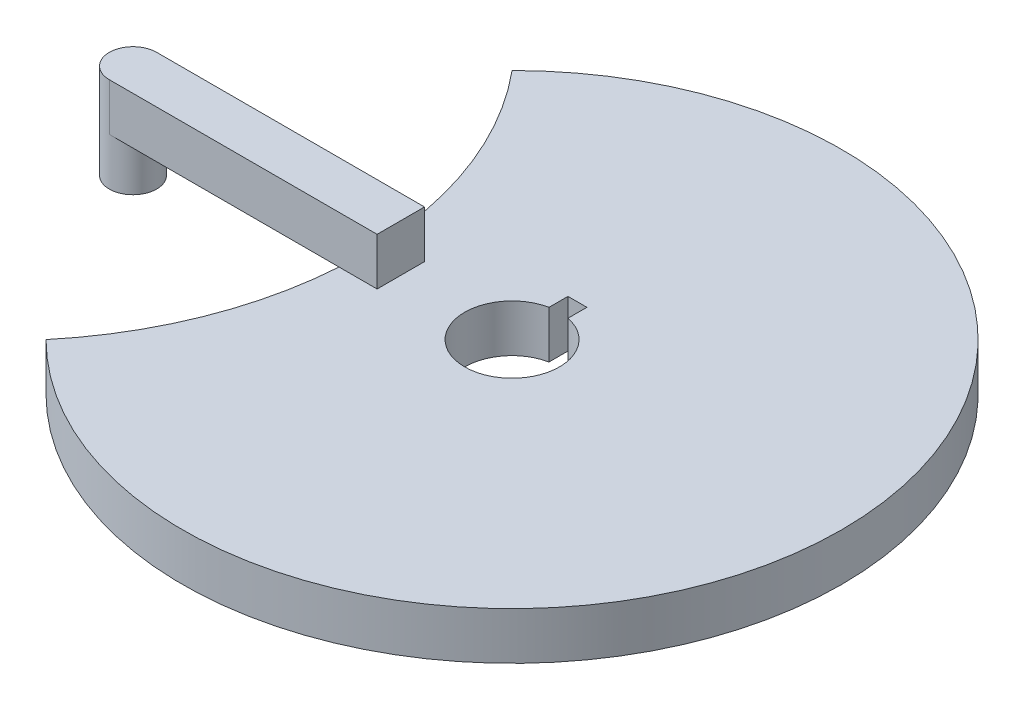
SolidWorks part; units mm, degrees
ref_plane "前视基准面" through (0, 0, 0) normal (0, 0, 1) x (1, 0, 0)
ref_plane "上视基准面" through (0, 0, 0) normal (0, 1, 0) x (1, 0, 0)
ref_plane "右视基准面" through (0, 0, 0) normal (1, 0, 0) x (0, 0, -1)
sketch "草图1" plane through (0, 0, 0) normal (0, 1, 0) x (1, 0, 0)
  line L0 (-129.4458, 0) -> (166.3539, 0) construction
  line L1 (0, 112.5965) -> (0, -118.4804) construction
  line L2 (-2, 9.798) -> (-2, 13.798)
  line L3 (-2, 13.798) -> (2, 13.798)
  line L4 (2, 9.798) -> (2, 13.798)
  line L5 (-49.1802, 49.1802) -> (0, 0) construction
  line L6 (0, 0) -> (-49.1802, -49.1802) construction
  arc A0 (-49.1802, -49.1802) -> (-49.1802, 49.1802) centre (0, 0) ccw
  arc A1 (-2, 9.798) -> (2, 9.798) centre (0, 0) ccw
  arc A5 (-49.1802, -49.1802) -> (-49.1802, 49.1802) centre (-108.1238, 0) ccw
  point P13 (0, 13.798)
  dimension "D1" = 4
  dimension "D2" = 90
  dimension "D3" = 10
  dimension "D4" = 4
extrude "凸台-拉伸1" add sketch "草图1" along normal blind 10
sketch "草图4" plane through (0, 10, 0) normal (0, 1, 0) x (1, 0, 0)
  line L0 (-80, 5) -> (-23.4813, 5)
  line L1 (-23.4813, 5) -> (-23.4813, -5)
  line L2 (-23.4813, -5) -> (-80, -5)
  arc A0 (-80, 5) -> (-80, -5) centre (-80, 0) ccw
  dimension "D1" = 80
extrude "凸台-拉伸5" add sketch "草图4" along normal blind 10
sketch "草图5" plane through (0, 10, 0) normal (0, -1, 0) x (1, 0, 0)
  circle A0 centre (-80, 0) radius 5
extrude "凸台-拉伸6" add sketch "草图5" along normal blind 10
